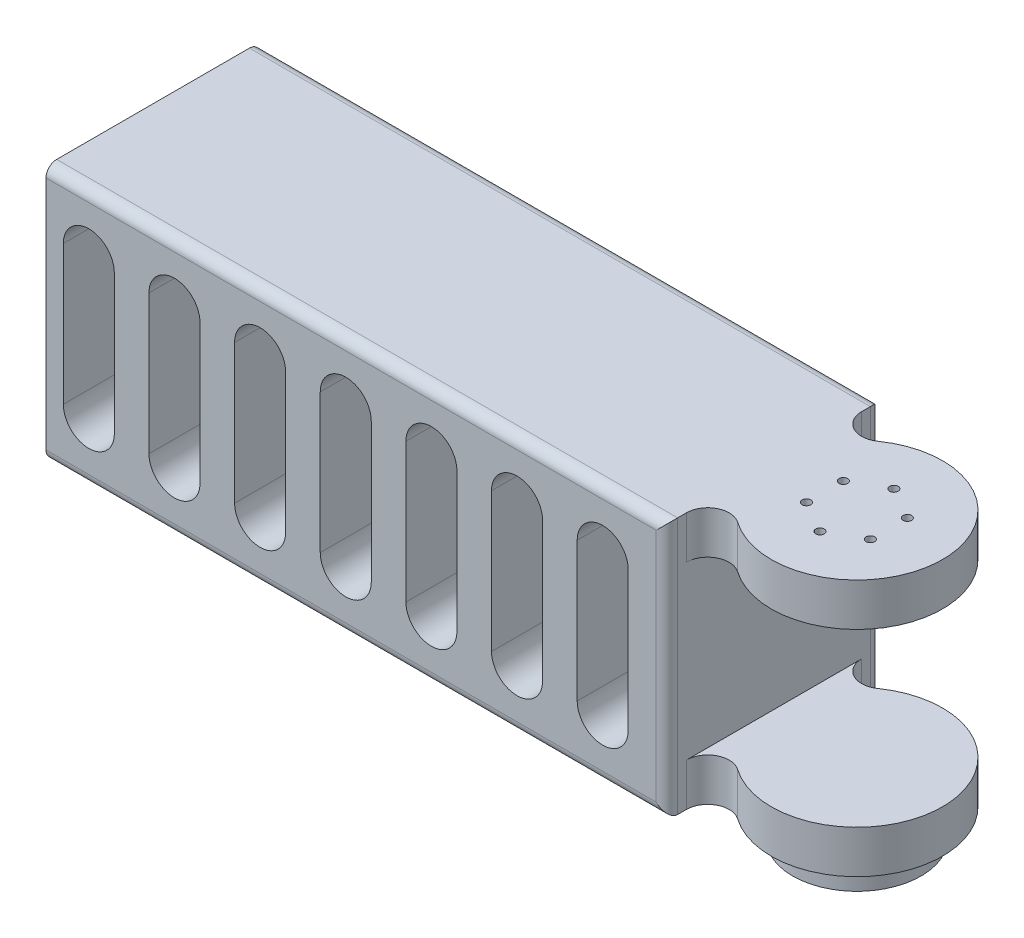
SolidWorks part; units mm, degrees
ref_plane "前视基准面" through (0, 0, 0) normal (0, 0, 1) x (1, 0, 0)
ref_plane "上视基准面" through (0, 0, 0) normal (0, 1, 0) x (1, 0, 0)
ref_plane "右视基准面" through (0, 0, 0) normal (1, 0, 0) x (0, 0, -1)
other "Configuration Table"
sketch "草图1" plane through (0, 0, 0) normal (0, 0, 1) x (1, 0, 0)
  line L1 (-150, 60) -> (150, 60)
  line L2 (-150, 60) -> (-150, -60)
  line L3 (-150, -60) -> (150, -60)
  line L4 (150, 60) -> (150, -60)
  line L5 (-150, 60) -> (150, -60) construction
  line L6 (-150, -60) -> (150, 60) construction
  point P0 (0, 0)
  dimension "D1" = 300
  dimension "D2" = 120
extrude "凸台-拉伸1" add sketch "草图1" along normal blind 100
sketch "草图2" plane through (0, 60, 0) normal (0, 1, 0) x (1, 0, 0)
  line L0 (150, -50) -> (150, -40)
  line L1 (150, -100) -> (150, 0) construction
  line L2 (150, -50) -> (150, -60)
  arc A0 (150, -40) -> (150, -60) centre (188.7298, -50) cw
extrude "凸台-拉伸2" add sketch "草图2" against normal blind 20
fillet "圆角2" radius 10 1 edges at (150, 50, 40)
fillet "圆角3" radius 10 1 edges at (150, 50, 60)
mirror "镜向6" about plane through (0, 0, 0) normal (1, 0, 0) of "凸台-拉伸2" second plane through (0, 0, 0) second plane normal (0, 1, 0)
fillet "圆角10" radius 10 1 edges at (150, -50, 60)
fillet "圆角11" radius 10 1 edges at (150, -50, 40)
fillet "圆角12" radius 10 1 edges at (-150, 50, 40)
fillet "圆角13" radius 10 1 edges at (-150, -50, 60)
fillet "圆角14" radius 10 1 edges at (-150, 50, 60)
fillet "圆角15" radius 10 1 edges at (-150, -50, 40)
sketch "草图3" plane through (0, 0, 100) normal (0, 0, 1) x (1, 0, 0)
  line L0 (0, -32.5116) -> (0, 32.5116) construction
  line L1 (0, -55) -> (0, 55) construction
  line L2 (-11.9162, -32.5116) -> (-11.9162, 32.5116)
  line L3 (11.9162, -32.5116) -> (11.9162, 32.5116)
  arc A0 (-11.9162, -32.5116) -> (11.9162, -32.5116) centre (0, -32.5116) ccw
  arc A1 (11.9162, 32.5116) -> (-11.9162, 32.5116) centre (0, 32.5116) ccw
  point P5 (0, 0)
extrude "切除-拉伸1" cut sketch "草图3" against normal up to next
pattern_linear "阵列(线性)1" count 4 spacing 40 along (1, 0, 0) count 4 spacing 40 along (-1, 0, 0) of "切除-拉伸1"
sketch "草图4" plane through (0, -60, 0) normal (0, -1, 0) x (1, 0, 0)
  circle A0 centre (188.7298, 50) radius 30
extrude "凸台-拉伸3" add sketch "草图4" along normal blind 13
sketch "草图6" plane through (0, 60, 0) normal (0, 1, 0) x (1, 0, 0)
  circle A0 centre (-188.7298, -50) radius 32.5
extrude "切除-拉伸2" cut sketch "草图6" against normal through all
fillet "圆角16" radius 5 8 edges at (150, 0, 0) (-150, 0, 0) (-150, 0, 100) (150, 0, 100) (0, -60, 0) (0, -60, 100) (0, 60, 0) (0, 60, 100)
sketch "草图10" plane through (-150, 0, 0) normal (-1, 0, 0) x (0, 0, 1)
  line L1 (-125.3906, 221.7049) -> (114.5446, 221.7049)
  line L2 (-125.3906, 221.7049) -> (-125.3906, -88.7722)
  line L3 (-125.3906, -88.7722) -> (114.5446, -88.7722)
  line L4 (114.5446, 221.7049) -> (114.5446, -88.7722)
  line L5 (-125.3906, 221.7049) -> (114.5446, -88.7722) construction
  line L6 (-125.3906, -88.7722) -> (114.5446, 221.7049) construction
  point P0 (-5.423, 66.4664)
extrude "切除-拉伸6" cut sketch "草图10" along normal through all and the other way blind 10
sketch "草图11" plane through (-140, 0, 0) normal (-1, 0, 0) x (0, 0, 1)
  circle A0 centre (90, 55.461) radius 2
extrude "切除-拉伸7" cut sketch "草图11" against normal blind 10
ref_plane "基准面2" through (0, 0, 50) normal (0, 0, 1) x (1, 0, 0)
mirror "镜向8" about plane through (0, 0, 0) normal (0, 1, 0) of "切除-拉伸7" second plane through (0, 0, 50) second plane normal (0, 0, 1)
sketch "草图12" plane through (0, 0, 0) normal (0, 1, 0) x (1, 0, 0)
  circle A1 centre (188.7298, -32.75) radius 2
extrude "切除-拉伸8" cut sketch "草图12" along normal through all
pattern_circular "阵列(圆周)2" count 6 over 360 about axis through (188.7298, 0, 50) along (0, 1, 0) of "切除-拉伸8"
